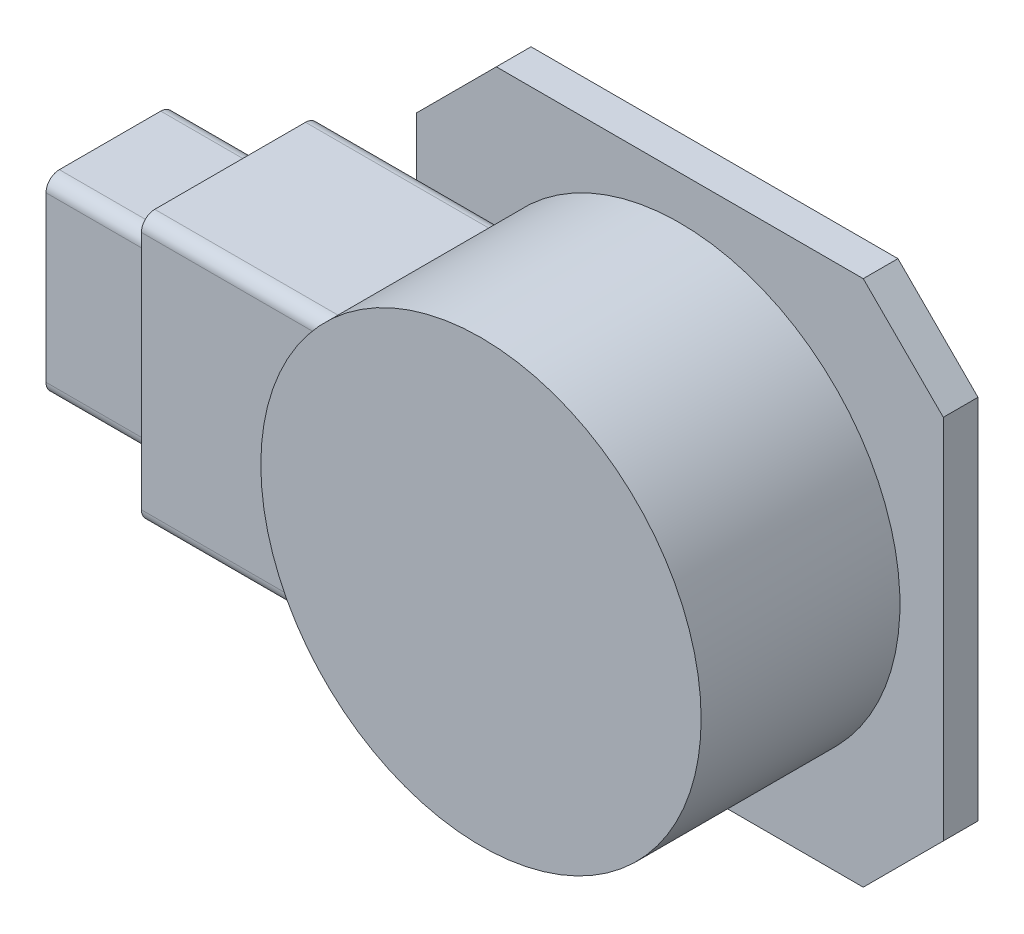
SolidWorks part; units mm, degrees
ref_plane "前基準面" through (0, 0, 0) normal (0, 0, 1) x (1, 0, 0)
ref_plane "上基準面" through (0, 0, 0) normal (0, 1, 0) x (1, 0, 0)
ref_plane "右基準面" through (0, 0, 0) normal (1, 0, 0) x (0, 0, -1)
sketch "草圖1" plane through (0, 0, 0) normal (0, 0, 1) x (1, 0, 0)
  line L0 (197.5, 137.5) -> (137.5, 197.5) construction
  line L1 (-110, 197.5) -> (110, 197.5) construction
  line L2 (-137.5, 197.5) -> (-197.5, 137.5) construction
  line L3 (-197.5, -110) -> (-197.5, 110) construction
  line L4 (-197.5, -137.5) -> (-137.5, -197.5) construction
  line L5 (110, -197.5) -> (-110, -197.5) construction
  line L6 (197.5, 137.5) -> (197.5, 110) construction
  line L7 (197.5, 110) -> (197.5, -110) construction
  line L8 (197.5, -110) -> (197.5, -137.5) construction
  line L9 (137.5, -197.5) -> (197.5, -137.5) construction
  line L10 (197.5, 137.5) -> (137.5, 197.5) construction
  line L11 (-110, 197.5) -> (110, 197.5) construction
  line L12 (-137.5, 197.5) -> (-197.5, 137.5) construction
  line L13 (-197.5, -110) -> (-197.5, 110) construction
  line L14 (-197.5, -137.5) -> (-137.5, -197.5) construction
  line L15 (110, -197.5) -> (-110, -197.5) construction
  line L16 (197.5, 137.5) -> (197.5, 110) construction
  line L17 (197.5, 110) -> (197.5, -110) construction
  line L18 (197.5, -110) -> (197.5, -137.5) construction
  line L19 (137.5, -197.5) -> (197.5, -137.5) construction
  line L20 (-197.5, 137.5) -> (-137.5, 197.5)
  line L21 (-137.5, 197.5) -> (137.5, 197.5)
  line L22 (137.5, 197.5) -> (197.5, 137.5)
  line L23 (197.5, 137.5) -> (197.5, -137.5)
  line L24 (197.5, -137.5) -> (137.5, -197.5)
  line L25 (137.5, -197.5) -> (-137.5, -197.5)
  line L26 (-137.5, -197.5) -> (-197.5, -137.5)
  line L27 (-197.5, -137.5) -> (-197.5, 137.5)
extrude "填料-伸長1" add sketch "草圖1" along normal blind 26
sketch "草圖3" plane through (0, 0, 26) normal (0, 0, 1) x (1, 0, 0)
  circle A0 centre (0, 0) radius 165 construction
  circle A1 centre (0, 0) radius 165
extrude "填料-伸長2" add sketch "草圖3" along normal blind 149
sketch "草圖4" plane through (0, 0, 0) normal (1, 0, 0) x (0, 0, -1)
  line L0 (-26, 90) -> (-26, -90) construction
  line L1 (-36, 100) -> (-149, 100)
  line L2 (-26, 90) -> (-26, -90)
  line L3 (-36, -100) -> (-149, -100)
  line L4 (-159, 90) -> (-159, -90)
  line L5 (-26, 100) -> (-159, -100) construction
  line L6 (-26, -100) -> (-159, 100) construction
  line L7 (0, 0) -> (-232.5569, 0) construction
  arc A0 (-36, 100) -> (-26, 90) centre (-36, 90) cw
  arc A1 (-26, -90) -> (-36, -100) centre (-36, -90) cw
  arc A2 (-149, -100) -> (-159, -90) centre (-149, -90) cw
  arc A3 (-149, 100) -> (-159, 90) centre (-149, 90) ccw
  point P0 (-92.5, 0)
  dimension "D3" = 10
  dimension "D1" = 133
  dimension "D2" = 200
extrude "填料-伸長3" add sketch "草圖4" against normal blind 270.5
sketch "草圖5" plane through (-270.5, 0, 0) normal (-1, 0, 0) x (0, 0, 1)
  line L0 (26, -90) -> (26, 90) construction
  line L1 (54.5, 71.5) -> (130.5, 71.5)
  line L2 (44.5, 61.5) -> (44.5, -61.5)
  line L3 (54.5, -71.5) -> (130.5, -71.5)
  line L4 (140.5, 61.5) -> (140.5, -61.5)
  line L5 (44.5, 71.5) -> (140.5, -71.5) construction
  line L6 (44.5, -71.5) -> (140.5, 71.5) construction
  line L7 (0, 0) -> (140.5, 0) construction
  line L8 (0, 95) -> (0, -95) construction
  arc A0 (44.5, -61.5) -> (54.5, -71.5) centre (54.5, -61.5) ccw
  arc A1 (130.5, -71.5) -> (140.5, -61.5) centre (130.5, -61.5) ccw
  arc A2 (54.5, 71.5) -> (44.5, 61.5) centre (54.5, 61.5) ccw
  arc A3 (130.5, 71.5) -> (140.5, 61.5) centre (130.5, 61.5) cw
  point P0 (92.5, 0)
  dimension "D4" = 10
  dimension "D1" = 96
  dimension "D2" = 143
  dimension "D3" = 18.5
extrude "填料-伸長4" add sketch "草圖5" along normal blind 90
